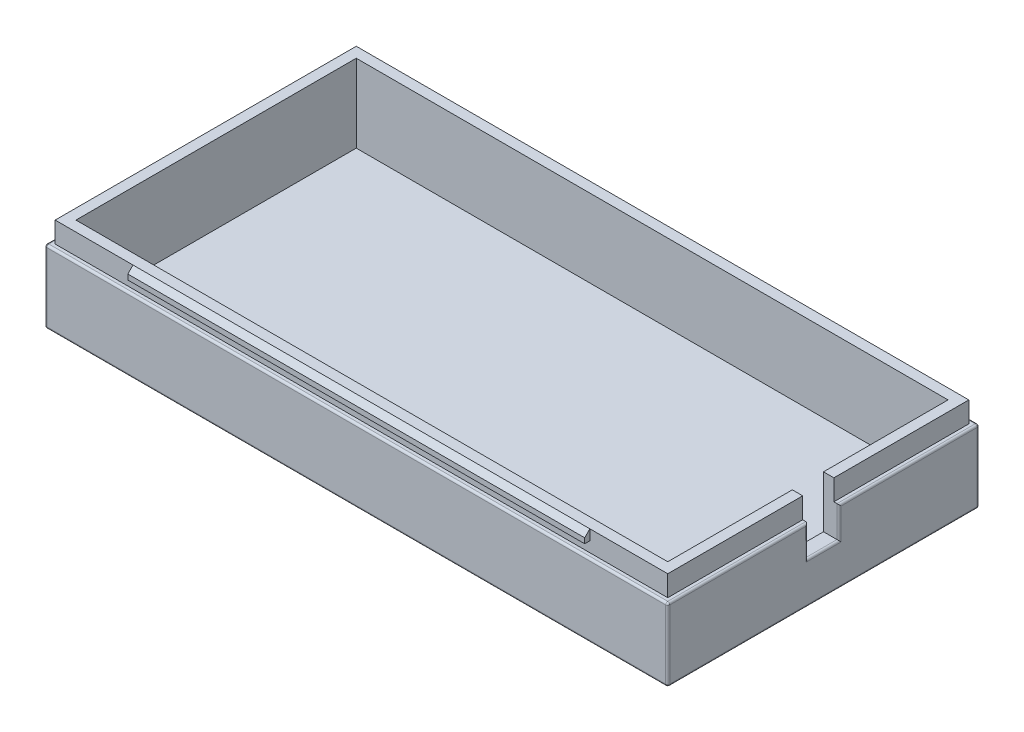
SolidWorks part; units mm, degrees
ref_plane "前视基准面" through (0, 0, 0) normal (0, 0, 1) x (1, 0, 0)
ref_plane "上视基准面" through (0, 0, 0) normal (0, 1, 0) x (1, 0, 0)
ref_plane "右视基准面" through (0, 0, 0) normal (1, 0, 0) x (0, 0, -1)
sketch "草图1" plane through (0, 0, 0) normal (0, 1, 0) x (1, 0, 0)
  line L0 (30, 15) -> (30, -15)
  line L1 (30, 15) -> (-30, 15)
  line L2 (30, -15) -> (-30, -15)
  line L3 (-30, 15) -> (-30, -15)
  line L4 (30, 15) -> (-30, -15) construction
  line L5 (30, -15) -> (-30, 15) construction
  point P1 (0, 0)
  dimension "D1" = 60
  dimension "D2" = 30
extrude "凸台-拉伸1" add sketch "草图1" along normal blind 7
sketch "草图2" plane through (0, 7, 0) normal (0, 1, 0) x (1, 0, 0)
  line L8 (29.5, 14.5) -> (-29.5, 14.5)
  line L9 (-29.5, 14.5) -> (-29.5, -14.5)
  line L10 (-29.5, -14.5) -> (29.5, -14.5)
  line L11 (29.5, -14.5) -> (29.5, 14.5)
  line L12 (29.5, 14.5) -> (-29.5, 14.5)
  line L13 (-29.5, 14.5) -> (-29.5, -14.5)
  line L14 (-29.5, -14.5) -> (29.5, -14.5)
  line L15 (29.5, -14.5) -> (29.5, 14.5)
  dimension "D1" = 0.5
extrude "凸台-拉伸2" add sketch "草图2" along normal blind 2
sketch "草图3" plane through (0, 9, 0) normal (0, 1, 0) x (1, 0, 0)
  line L8 (28.5, -13.5) -> (28.5, 13.5)
  line L9 (28.5, 13.5) -> (-28.5, 13.5)
  line L10 (-28.5, 13.5) -> (-28.5, -13.5)
  line L11 (-28.5, -13.5) -> (28.5, -13.5)
  line L12 (28.5, -13.5) -> (28.5, 13.5)
  line L13 (28.5, 13.5) -> (-28.5, 13.5)
  line L14 (-28.5, 13.5) -> (-28.5, -13.5)
  line L15 (-28.5, -13.5) -> (28.5, -13.5)
  dimension "D1" = 1
extrude "切除-拉伸1" cut sketch "草图3" against normal blind 7.5
sketch "草图4" plane through (0, 0, -14.5) normal (0, 0, -1) x (-1, 0, 0)
  line L0 (-29.5, 9) -> (29.5, 9) construction
  line L1 (-22, 9) -> (22, 9)
  line L2 (-22, 9) -> (-22, 8)
  line L3 (-22, 8) -> (22, 8)
  line L4 (22, 9) -> (22, 8)
  line L5 (-30, 7) -> (-30, 0) construction
  line L6 (30, 7) -> (30, 0) construction
  dimension "D1" = 8
  dimension "D2" = 8
  dimension "D3" = 1
extrude "凸台-拉伸3" add sketch "草图4" along normal blind 0.5
chamfer "倒角1" distance 0.5 angle 45 1 edges at (0, 9, -15)
mirror "镜向1" about plane through (0, 0, 0) normal (0, 0, 1) of "凸台-拉伸3", "倒角1"
sketch "草图5" plane through (0, 9, 0) normal (0, 1, 0) x (1, 0, 0)
  line L0 (0, 0) -> (30, 0) construction
  line L1 (30, -15) -> (30, 15) construction
  line L2 (30, 0) -> (30, 1.5)
  line L3 (30, 1.5) -> (28.5, 1.5)
  line L4 (28.5, -13.5) -> (28.5, 13.5) construction
  line L5 (28.5, 1.5) -> (28.5, -1.5)
  line L6 (28.5, -1.5) -> (30, -1.5)
  line L7 (30, -1.5) -> (30, 0)
  dimension "D1" = 1.5
  dimension "D2" = 1.5
extrude "切除-拉伸2" cut sketch "草图5" against normal blind 5
fillet "圆角1" radius 0.2 16 edges at (30, 5.5, -1.5) (30, 7, -8.25) (30, 7, 8.25) (30, 5.5, 1.5) (30, 4, 0) (0, 7, 15) (30, 3.5, 15) (-30, 7, 0) (-30, 3.5, 15) (30, 3.5, -15) (0, 7, -15) (-30, 3.5, -15) (-30, 0, 0) (0, 0, 15) (30, 0, 0) (0, 0, -15)
